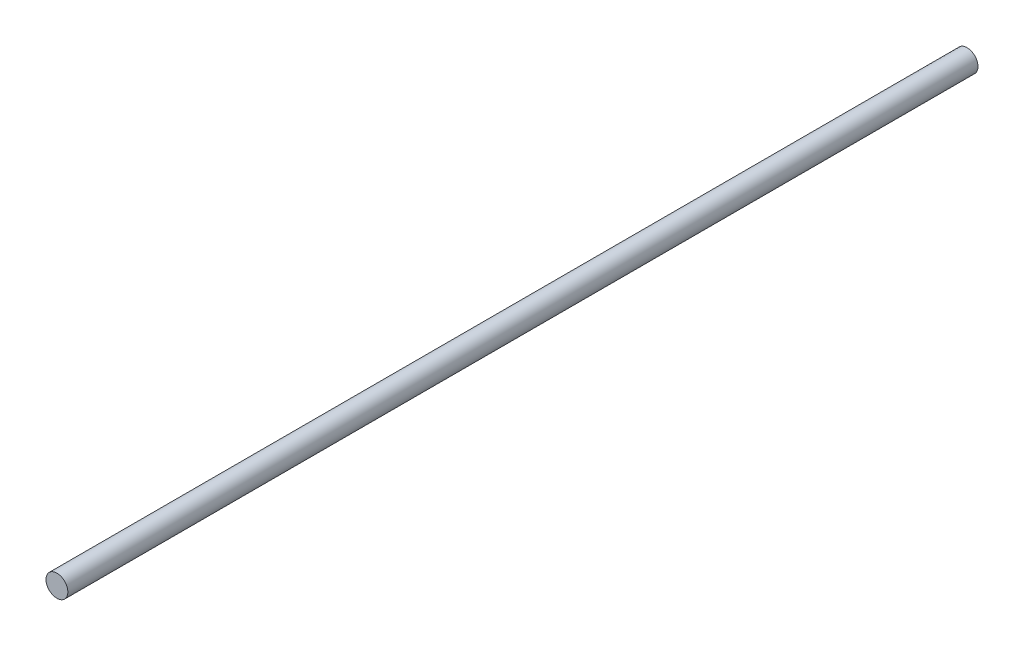
SolidWorks part; units mm, degrees
ref_plane "Piano frontale" through (0, 0, 0) normal (0, 0, 1) x (1, 0, 0)
ref_plane "Piano superiore" through (0, 0, 0) normal (0, 1, 0) x (1, 0, 0)
ref_plane "Piano destro" through (0, 0, 0) normal (1, 0, 0) x (0, 0, -1)
sketch "Schizzo1" plane through (0, 0, 0) normal (0, 0, 1) x (1, 0, 0)
  circle A0 centre (0, 0) radius 6
  dimension "D1" = 12
extrude "Estrusione-Estrusione1" add sketch "Schizzo1" along normal blind 500
cosmetic thread "Filettatura cosmetica1" parameters "D2"=10.072
cosmetic thread "Filettatura cosmetica2" parameters "D1"=5, "D2"=4.891
